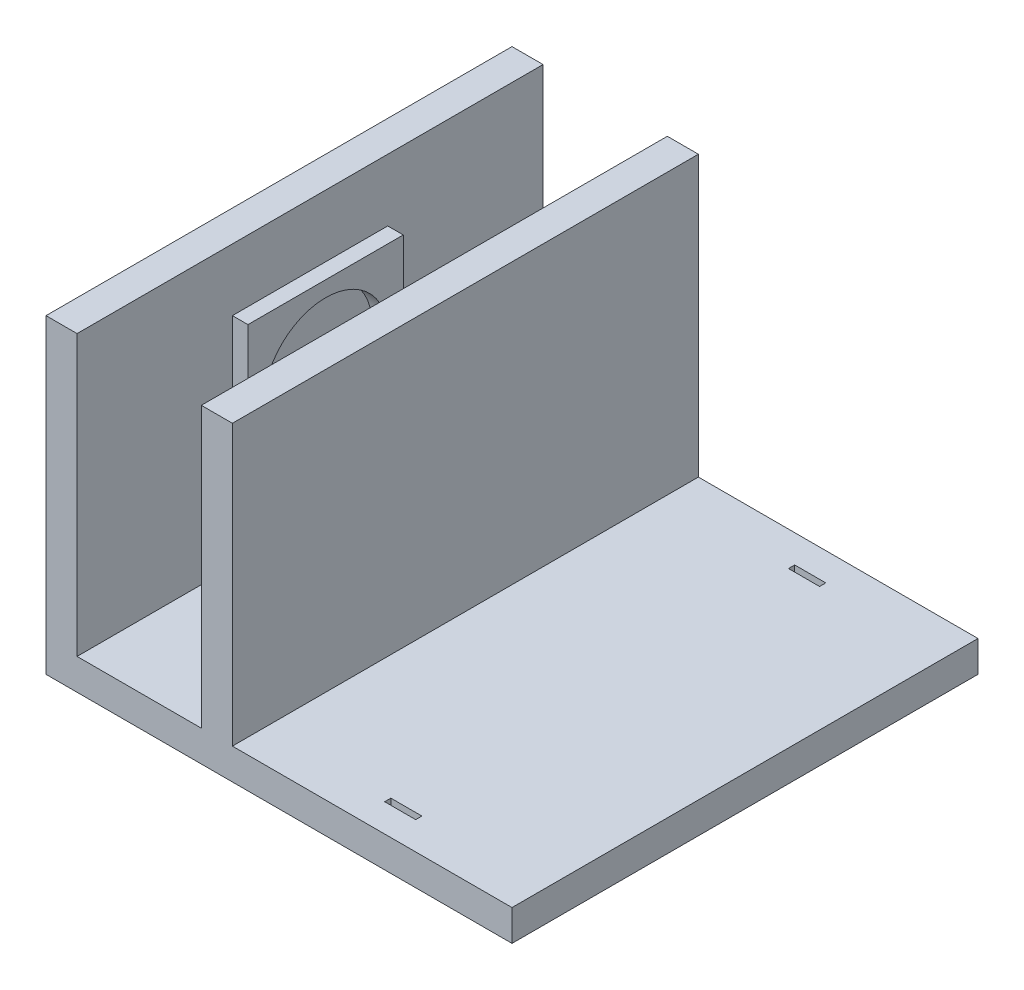
SolidWorks part; units mm, degrees
material "Balsa"
ref_plane "Front Plane" through (0, 0, 0) normal (0, 0, 1) x (1, 0, 0)
ref_plane "Top Plane" through (0, 0, 0) normal (0, 1, 0) x (1, 0, 0)
ref_plane "Right Plane" through (0, 0, 0) normal (1, 0, 0) x (0, 0, -1)
sketch "Sketch1" plane through (0, 0, 0) normal (0, 0, 1) x (1, 0, 0)
  line L0 (50, 10) -> (50, 100)
  line L1 (0, 0) -> (150, 0)
  line L2 (0, 0) -> (0, 10)
  line L3 (10, 10) -> (50, 10)
  line L4 (150, 0) -> (150, 10)
  line L5 (0, 0) -> (10, 0)
  line L6 (0, 0) -> (0, 100)
  line L7 (0, 100) -> (10, 100)
  line L8 (10, 10) -> (10, 100)
  line L9 (150, 10) -> (60, 10)
  line L25 (60, 10) -> (60, 100)
  line L26 (50, 100) -> (60, 100)
  line L27 (60, 0) -> (60, 100) construction
  line L28 (50, 0) -> (50, 100) construction
  line L29 (10, 0) -> (10, 100) construction
  line L30 (60, 10) -> (150, 10)
  dimension "D2" = 10
  dimension "D3" = 10
  dimension "D4" = 100
  dimension "D5" = 40
  dimension "D6" = 10
  dimension "D7" = 150
extrude "Boss-Extrude1" add sketch "Sketch1" along normal blind 150
sketch "Sketch3" plane through (0, 10, 0) normal (0, 1, 0) x (1, 0, 0)
  line L0 (105, -150) -> (105, 0) construction
  line L1 (150, -75) -> (60, -75) construction
  line L2 (110, -141) -> (110, -139)
  line L3 (110, -141) -> (100, -141)
  line L4 (150, 0) -> (60, 0)
  line L5 (60, 0) -> (60, -150)
  line L6 (60, -150) -> (150, -150)
  line L7 (150, -150) -> (150, 0)
  line L8 (150, 0) -> (60, 0)
  line L9 (60, 0) -> (60, -150)
  line L10 (60, -150) -> (150, -150)
  line L11 (150, -150) -> (150, 0)
  line L12 (110, -139) -> (100, -139)
  line L13 (100, -141) -> (100, -139)
  line L14 (105, -139) -> (105, -141) construction
  line L15 (110, -140) -> (100, -140) construction
  line L16 (110, -9) -> (110, -11)
  line L17 (100, -9) -> (100, -11)
  line L18 (110, -11) -> (100, -11)
  line L19 (110, -9) -> (100, -9)
  point P9 (105, -140)
  dimension "D2" = 10
  dimension "D3" = 2
  dimension "D4" = 10
  dimension "D1" = 0
extrude "Cut-Extrude1" cut sketch "Sketch3" against normal blind 10 contours L16 L19 L17 L18 | L3 L13 L12 L2
sketch "Sketch4" plane through (10, 0, 0) normal (1, 0, 0) x (0, 0, -1)
  line L0 (-150, 100) -> (0, 10) construction
  line L1 (0, 100) -> (-150, 10) construction
  line L3 (-100, 30) -> (-50, 30)
  line L4 (0, 10) -> (0, 100)
  line L5 (0, 100) -> (-150, 100)
  line L6 (-150, 100) -> (-150, 10)
  line L7 (-150, 10) -> (0, 10)
  line L8 (0, 10) -> (0, 100)
  line L9 (0, 100) -> (-150, 100)
  line L10 (-150, 100) -> (-150, 10)
  line L11 (-150, 10) -> (0, 10)
  line L12 (-100, 30) -> (-100, 80)
  line L13 (-100, 80) -> (-50, 80)
  line L14 (-50, 30) -> (-50, 80)
  line L15 (-100, 30) -> (-50, 80) construction
  line L16 (-100, 80) -> (-50, 30) construction
  circle A0 centre (-75, 55) radius 20
  point P2 (-75, 55)
  dimension "D3" = 40
  dimension "D2" = 50
  dimension "D1" = 0
extrude "Boss-Extrude2" add sketch "Sketch4" along normal blind 5 contours L3 L14 L13 L12 A0
sketch "Sketch5" plane through (50, 0, 0) normal (-1, 0, 0) x (0, 0, 1)
  line L4 (0, 100) -> (0, 10)
  line L5 (150, 100) -> (0, 100)
  line L6 (150, 10) -> (150, 100)
  line L7 (0, 10) -> (150, 10)
  line L8 (0, 100) -> (0, 10)
  line L9 (150, 100) -> (0, 100)
  line L10 (150, 10) -> (150, 100)
  line L11 (0, 10) -> (150, 10)
  line L12 (50, 30) -> (100, 30)
  line L13 (50, 80) -> (50, 30)
  line L14 (100, 80) -> (50, 80)
  line L15 (100, 30) -> (100, 80)
  line L16 (50, 30) -> (100, 30)
  line L17 (50, 80) -> (50, 30)
  line L18 (100, 80) -> (50, 80)
  line L19 (100, 30) -> (100, 80)
  circle A1 centre (75, 55) radius 20
  circle A2 centre (75, 55) radius 20
  dimension "D1" = 0
  dimension "D2" = 0
  dimension "D3" = 0
extrude "Boss-Extrude3" add sketch "Sketch5" along normal blind 5 contours L16 L19 L18 L17 A2
sketch "Sketch6" plane through (10, 0, 0) normal (1, 0, 0) x (0, 0, -1)
  circle A0 centre (-75, 55) radius 1.5
  circle A1 centre (-75, 55) radius 20
  circle A2 centre (-75, 55) radius 20
  point P1 (0, 0)
  point P5 (0, 0)
  dimension "D2" = 3
  dimension "D1" = 0
extrude "Cut-Extrude2" cut sketch "Sketch6" against normal through all contours A0
